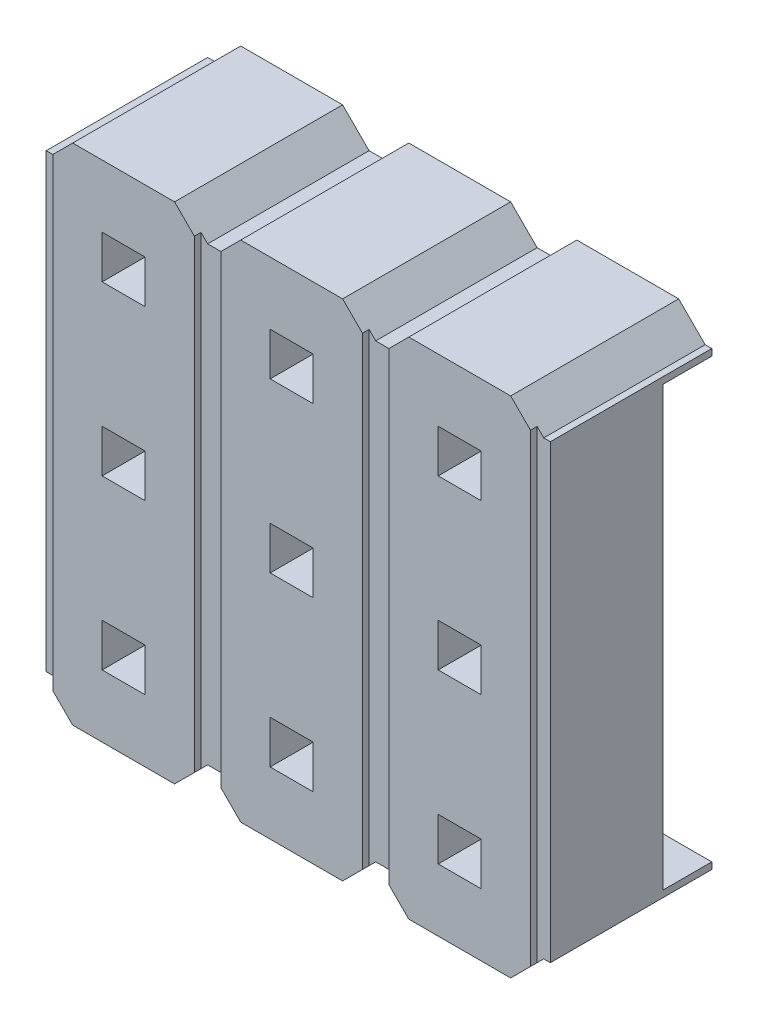
SolidWorks part; units mm, degrees
material "Nylon 6/10"
ref_plane "Face" through (0, 0, 0) normal (0, 0, 1) x (1, 0, 0)
ref_plane "Dessus" through (0, 0, 0) normal (0, 1, 0) x (1, 0, 0)
ref_plane "Droite" through (0, 0, 0) normal (1, 0, 0) x (0, 0, -1)
sketch "Esquisse1" plane through (0, 0, 0) normal (0, 0, 1) x (1, 0, 0)
  line L0 (0, 0) -> (-1.27, 0) construction
  line L1 (0, 0) -> (0, -3.81) construction
  line L2 (-1.27, -3.41) -> (-1.27, 3.41)
  line L3 (0.77, -3.81) -> (-0.77, -3.81)
  line L4 (-1.27, -3.41) -> (-1.17, -3.41)
  line L5 (-1.17, -3.41) -> (-0.77, -3.81)
  line L6 (0.77, 3.81) -> (-0.77, 3.81)
  line L7 (-1.17, 3.41) -> (-0.77, 3.81)
  line L8 (-1.27, 3.41) -> (-1.17, 3.41)
  line L9 (1.27, 3.41) -> (1.17, 3.41)
  line L10 (1.17, 3.41) -> (0.77, 3.81)
  line L11 (1.17, -3.41) -> (0.77, -3.81)
  line L12 (1.27, -3.41) -> (1.17, -3.41)
  line L13 (1.27, -3.41) -> (1.27, 3.41)
  point P13 (0, 3.81)
  dimension "D1" = 7.62
  dimension "D2" = 0.5
  dimension "D3" = 2.54
  dimension "D4" = 45
  dimension "D5" = 0.1
extrude "Boss.-Extru.1" add sketch "Esquisse1" along normal blind 2.54
sketch "Esquisse3" plane through (0, 0.04, 2.54) normal (0, 0, -1) x (1, 0, 0)
  line L8 (-1.27, -3.37) -> (-1.17, -3.37)
  line L9 (-1.17, -3.37) -> (-1.07, -3.47)
  line L10 (-0.77, -3.77) -> (-1.17, -3.37) construction
  line L11 (-1.07, -3.47) -> (-1.07, 3.55)
  line L12 (0, -3.77) -> (0, 3.85) construction
  line L15 (-1.17, 3.45) -> (-0.77, 3.85) construction
  line L16 (-1.07, 3.55) -> (-1.17, 3.45)
  line L17 (-1.17, 3.45) -> (-1.27, 3.45)
  line L18 (-1.27, 3.45) -> (-1.27, -3.37)
  line L19 (1.27, 3.45) -> (1.27, -3.37)
  line L20 (0.77, -3.77) -> (-0.77, -3.77) construction
  line L21 (-0.77, 3.85) -> (0.77, 3.85) construction
  line L22 (1.17, 3.45) -> (1.27, 3.45)
  line L23 (1.07, 3.55) -> (1.17, 3.45)
  line L24 (1.07, -3.47) -> (1.07, 3.55)
  line L25 (1.17, -3.37) -> (1.07, -3.47)
  line L26 (1.27, -3.37) -> (1.17, -3.37)
  dimension "D1" = 0.2
extrude "Enlèv. mat.-Extru.2" cut sketch "Esquisse3" along normal blind 0.1
sketch "Esquisse5" plane through (0, 0, 2.54) normal (0, 0, 1) x (1, 0, 0)
  line L0 (-0.77, -3.81) -> (0.77, -3.81) construction
  line L1 (-0.325, -2.865) -> (0.325, -2.865)
  line L2 (-0.325, -2.865) -> (-0.325, -2.215)
  line L3 (-0.325, -2.215) -> (0.325, -2.215)
  line L4 (0.325, -2.865) -> (0.325, -2.215)
  point P0 (0, -2.215)
  point P10 (-0.325, -2.54)
  dimension "D1" = 0.65
  dimension "D2" = 1.27
extrude "Enlèv. mat.-Extru.3" cut sketch "Esquisse5" against normal through all
pattern_linear "Répétition linéaire1" count 3 spacing 2.54 along (0, 1, 0) of "Enlèv. mat.-Extru.3"
pattern_linear "Répétition linéaire" count 3 spacing 2.54 along (1, 0, 0) of "Boss.-Extru.1", "Enlèv. mat.-Extru.2", "Enlèv. mat.-Extru.3", "Répétition linéaire1"
sketch "Esquisse2" plane through (-1.27, 0, 0) normal (1, 0, 0) x (0, 0, -1)
  line L1 (-0.74, -3.31) -> (0, -3.31)
  line L2 (-0.74, -3.31) -> (-0.74, 3.31)
  line L3 (-0.74, 3.31) -> (0, 3.31)
  line L4 (0, -3.31) -> (0, 3.31)
  line L8 (-2.44, 3.41) -> (0, 3.41) construction
  line L9 (-2.54, 3.51) -> (-2.54, -3.51) construction
  dimension "D1" = 0.1
  dimension "D2" = 1.8
extrude "Enlèv. mat.-Extru.1" cut sketch "Esquisse2" along normal through all
equation "\"D2@Esquisse5\"=\"D3@Esquisse1\"/2"
equation "\"D3@Répétition linéaire1\"=\"D3@Esquisse1\""
